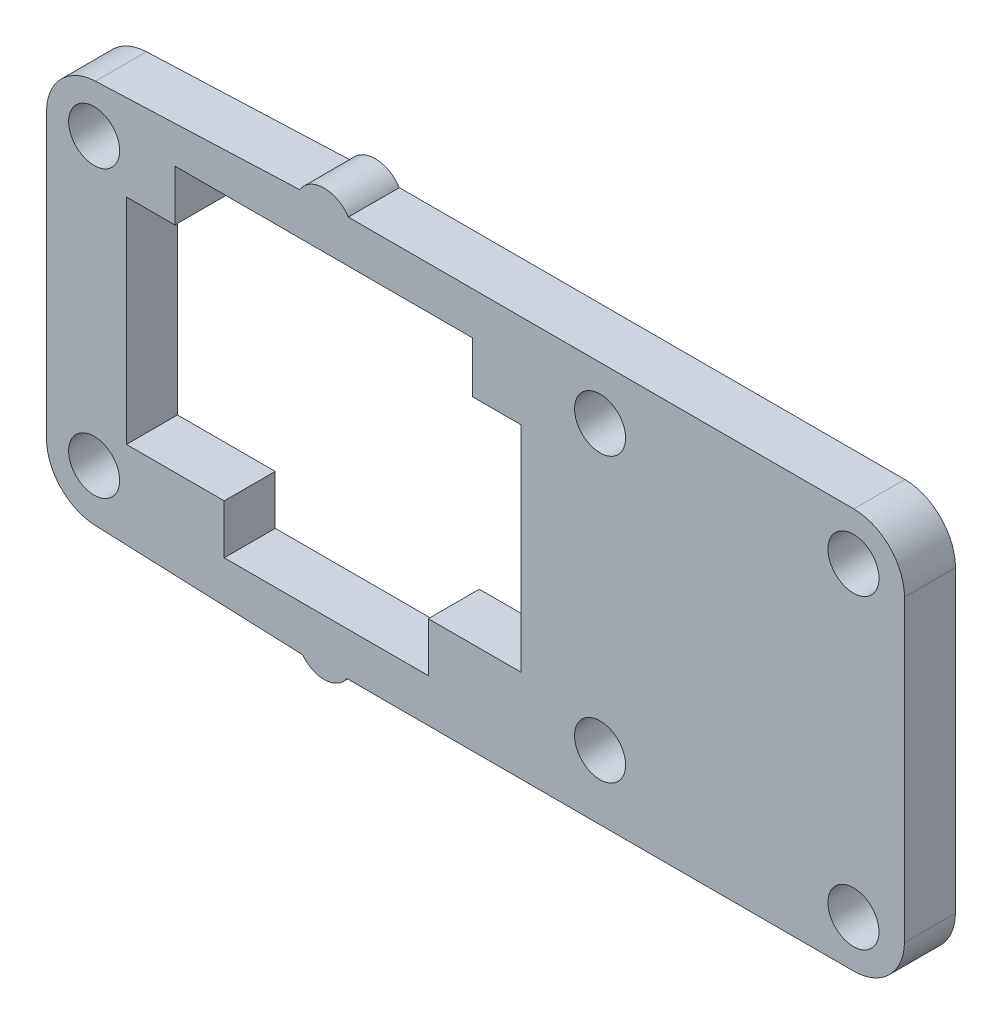
SolidWorks part; units mm, degrees
ref_plane "Front Plane" through (0, 0, 0) normal (0, 0, 1) x (1, 0, 0)
ref_plane "Top Plane" through (0, 0, 0) normal (0, 1, 0) x (1, 0, 0)
ref_plane "Right Plane" through (0, 0, 0) normal (1, 0, 0) x (0, 0, -1)
sketch "Sketch1" plane through (0, 0, 0) normal (0, 0, 1) x (1, 0, 0)
  line L16 (44.6717, 20.1342) -> (14.9487, 20.1342)
  line L17 (12.0869, 20.1) -> (0.0797, 19.6187)
  line L18 (-2.8, 16.6553) -> (-2.8, 0.0131)
  line L19 (0.2527, -3.0187) -> (12.2599, -3.5)
  line L20 (14.8621, -3.4089) -> (44.5851, -3.4089)
  line L21 (47.65, -0.4658) -> (47.65, 17.1342)
  line L27 (4.75, 14.6342) -> (1.9, 14.6342)
  line L28 (1.9, 14.6342) -> (1.9, 2.0342)
  line L29 (1.9, 2.0342) -> (7.65, 2.0342)
  line L30 (7.65, 2.0342) -> (7.65, -0.8658)
  line L31 (7.65, -0.8658) -> (19.65, -0.8658)
  line L32 (19.65, -0.8658) -> (19.65, 2.0342)
  line L33 (19.65, 2.0342) -> (25.1, 2.0342)
  line L34 (25.1, 14.6342) -> (22.25, 14.6342)
  line L35 (25.1, 2.0342) -> (25.1, 14.6342)
  line L36 (22.25, 17.6342) -> (4.75, 17.6342)
  line L37 (22.25, 14.6342) -> (22.25, 17.6342)
  line L39 (4.75, 17.6342) -> (4.75, 14.6342)
  arc A12 (47.65, 17.1342) -> (44.6717, 20.1342) centre (44.65, 17.1343) ccw
  arc A13 (14.9487, 20.1342) -> (12.0869, 20.1) centre (13.5287, 19.2014) ccw
  arc A14 (0.0797, 19.6187) -> (-2.8, 16.6553) centre (0.1998, 16.6211) ccw
  arc A15 (-2.8, 0.0131) -> (0.2527, -3.0187) centre (0.1998, -0.0192) ccw
  arc A16 (12.2599, -3.5) -> (14.8621, -3.4089) centre (13.5287, -2.533) ccw
  arc A17 (44.5851, -3.4089) -> (47.65, -0.4658) centre (44.6505, -0.4096) ccw
  circle A18 centre (29.75, 17.0266) radius 1.5
  circle A19 centre (44.65, 17.3342) radius 1.5
  circle A20 centre (44.65, -0.6658) radius 1.5
  circle A21 centre (29.75, 0.3835) radius 1.5
  circle A22 centre (0, 0) radius 1.5
  circle A23 centre (0, 16.7876) radius 1.5
  dimension "D3" = 3
  dimension "D4" = 3
  dimension "D13" = 1.699
  dimension "D22" = 2.5
  dimension "D28" = 3
  dimension "D30" = 3.0187
  dimension "D2" = 16.6423
  dimension "D5" = 17.6
  dimension "D6" = 29.723
  dimension "D7" = 12.0168
  dimension "D8" = 92.295
  dimension "D9" = 90
  dimension "D10" = 12
  dimension "D11" = 5.75
  dimension "D12" = 5.45
  dimension "D14" = 12.6
  dimension "D15" = 2.9
  dimension "D16" = 14.9
  dimension "D17" = 17.5
  dimension "D18" = 21.7344
  dimension "D19" = 2.85
  dimension "D20" = 3
  dimension "D21" = 18
  dimension "D23" = 0.9328
  dimension "D24" = 3.1076
  dimension "D25" = 3
  dimension "D26" = 3
  dimension "D27" = 2.8
  dimension "D29" = 16.6211
  dimension "D31" = 2.8311
  dimension "D32" = 2.8
  dimension "D33" = 2.8
  dimension "D34" = 3.7924
  dimension "D35" = 4.7
  dimension "D36" = 17.9
extrude "Boss-Extrude1" add sketch "Sketch1" along normal blind 3 contours L16 A13 L17 A14 L18 A15 L19 A16 L20 A17 L21 A12
